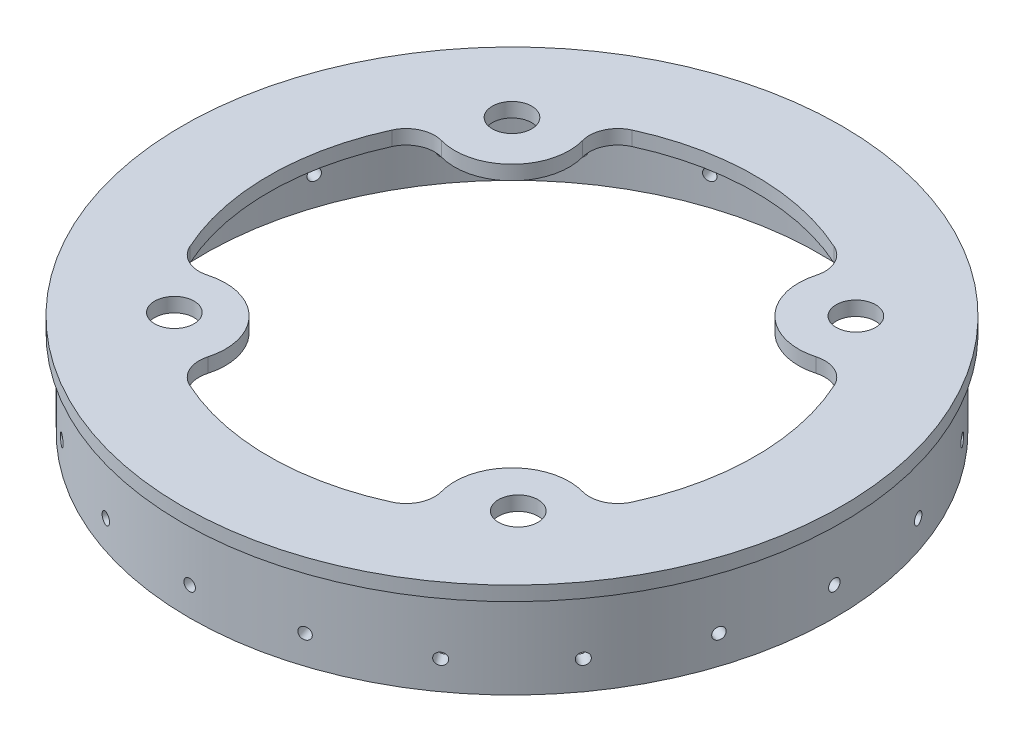
SolidWorks part; units mm, degrees
material "6061-T6 (SS)"
ref_plane "Front Plane" through (0, 0, 0) normal (0, 0, 1) x (1, 0, 0)
ref_plane "Top Plane" through (0, 0, 0) normal (0, 1, 0) x (1, 0, 0)
ref_plane "Right Plane" through (0, 0, 0) normal (1, 0, 0) x (0, 0, -1)
sketch "Sketch1" plane through (0, 0, 0) normal (0, 0, 1) x (1, 0, 0)
  line L0 (149.225, 95.8681) -> (149.225, -49.5637) construction
  line L1 (136.525, 0) -> (142.875, 0)
  line L2 (142.875, 0) -> (142.875, 38.1)
  line L3 (142.875, 38.1) -> (146.05, 38.1)
  line L4 (146.05, 38.1) -> (146.05, 44.45)
  line L5 (146.05, 44.45) -> (136.525, 44.45)
  line L6 (136.525, 44.45) -> (136.525, 0)
  line L7 (0, 75.5952) -> (0, -40.7001) construction
  dimension "D1" = 136.525
  dimension "D2" = 9.525
  dimension "D3" = 6.35
  dimension "D4" = 3.175
  dimension "D5" = 6.35
  dimension "D6" = 44.45
revolve "Revolve1" add sketch "Sketch1" angle 360 about L7
ref_plane "Plane1" through (-142.875, 0, 0) normal (-1, 0, 0) x (0, 0, 1)
sketch "Sketch4" plane through (-142.875, 0, 0) normal (-1, 0, 0) x (0, 0, 1)
  line L0 (-142.875, 38.1) -> (142.875, 38.1) construction
  line L1 (-142.875, 0) -> (142.875, 0) construction
  line L2 (-142.875, 38.1) -> (142.875, 38.1) construction
  line L3 (-142.875, 0) -> (142.875, 0) construction
  line L4 (0, 77.7064) -> (0, -55.6061) construction
hole_wizard "1/4-20 Tapped Hole1" positions "3DSketch1" profile "Sketch5" tap size "1/4-20" standard "ANSI Inch"
sketch3d "3DSketch1"
  line L0 (-142.875, 77.7064, 0) -> (-142.875, -55.6061, 0) construction
  line L1 (-142.875, 0, -142.875) -> (-142.875, 0, 142.875) construction
  point P0 (-142.875, 12.7, 0)
  dimension "D1" = 12.7
sketch "Sketch5" plane through (-142.875, 12.7, 0) normal (0, 1, 0) x (0, 0, 1)
  line L0 (0, 0) -> (0, 314.9078)
  line L1 (0, 314.9078) -> (2.5527, 314.9078)
  line L2 (2.5527, 314.9078) -> (2.5527, 0)
  line L5 (2.5527, 0) -> (0, 0)
  line L11 (0, -6.35) -> (0, 107.95) construction
  dimension "Thread Major Dia." = 5.1054
  dimension "Thru Tap Drill Depth" = 314.9078
pattern_circular "CirPattern2" count 20 over 360 about axis through (0, 75.5952, 0) along (0, 1, 0) of "1/4-20 Tapped Hole1"
sketch "Sketch6" plane through (0, 44.45, 0) normal (0, 1, 0) x (1, 0, 0)
  line L0 (-224.8129, 0) -> (107.7631, 0) construction
  line L1 (0, 113.3938) -> (0, -91.3137) construction
  arc A0 (-91.9187, 56.248) -> (-56.248, 91.9187) centre (-76.2, 76.2) ccw
  arc A1 (56.248, 91.9187) -> (91.9187, 56.248) centre (76.2, 76.2) ccw
  arc A2 (91.9187, -56.248) -> (56.248, -91.9187) centre (76.2, -76.2) ccw
  arc A3 (-56.248, -91.9187) -> (-91.9187, -56.248) centre (-76.2, -76.2) ccw
  arc A4 (-56.248, -91.9187) -> (56.248, -91.9187) centre (0, 0) ccw
  arc A5 (-91.9187, 56.248) -> (-91.9187, -56.248) centre (0, 0) ccw
  arc A6 (56.248, 91.9187) -> (-56.248, 91.9187) centre (0, 0) ccw
  arc A7 (91.9187, -56.248) -> (91.9187, 56.248) centre (0, 0) ccw
  circle A8 centre (0, 0) radius 136.525 construction
  circle A9 centre (0, 0) radius 136.525
  dimension "D5" = 50.8
  dimension "D6" = 215.5261
  dimension "D1" = 152.4
  dimension "D2" = 152.4
  dimension "D3" = 76.2
  dimension "D4" = 76.2
extrude "Boss-Extrude1" add sketch "Sketch6" against normal blind 6.35
fillet "Fillet1" radius 12.7 8 edges at (-91.9187, 41.275, -56.248) (-56.248, 41.275, -91.9187) (56.248, 41.275, -91.9187) (91.9187, 41.275, -56.248) (91.9187, 41.275, 56.248) (56.248, 41.275, 91.9187) (-91.9187, 41.275, 56.248) (-56.248, 41.275, 91.9187)
sketch "Sketch7" plane through (0, 38.1, 0) normal (0, -1, 0) x (1, 0, 0)
  line L0 (-110.9123, 79.6086) -> (-83.0428, 51.7391)
  line L1 (-79.6086, 110.9123) -> (-51.7391, 83.0428)
  line L2 (-132.8233, 132.8233) -> (131.7271, -131.7271) construction
  line L3 (0, 61.9556) -> (0, -61.9427) construction
  circle A0 centre (0, 0) radius 136.525 construction
  circle A2 centre (0, 0) radius 136.525
  circle A3 centre (0, 0) radius 136.525
  dimension "D2" = 45
  dimension "D1" = 0
chamfer "Chamfer1" distance 12.7 angle 45 1 edges at (0, 38.1, 136.525)
sketch "Sketch9" plane through (0, 44.45, 0) normal (0, 1, 0) x (1, 0, 0)
  point P0 (-76.2, 76.2)
  point P1 (76.2, 76.2)
  point P2 (76.2, -73.4305)
  point P3 (-76.2, -73.4305)
  dimension "D1" = 152.4
  dimension "D3" = 76.2
  dimension "D2" = 76.2
hole_wizard "3/4-16 Tapped Hole1" positions "3DSketch3" profile "Sketch10" tap size "3/4-16" standard "ANSI Inch" end condition through all
sketch3d "3DSketch3"
  point P0 (-76.2, 44.45, -76.2)
  point P3 (-76.2, 44.45, 73.4305)
  point P6 (76.2, 44.45, 73.4305)
  point P9 (76.2, 44.45, -76.2)
sketch "Sketch10" plane through (-76.2, 44.45, -76.2) normal (1, 0, 0) x (0, 0, 1)
  line L0 (0, 0) -> (0, 44.45)
  line L1 (0, 44.45) -> (8.7312, 44.45)
  line L2 (8.7312, 44.45) -> (8.7312, 0)
  line L5 (8.7312, 0) -> (0, 0)
  line L11 (0, -6.35) -> (0, 107.95) construction
  dimension "Thru Tap Drill Dia." = 17.4625
  dimension "Thru Tap Drill Depth" = 44.45
cosmetic thread "Hole Thread1" parameters "D2"=19.05
cosmetic thread "Hole Thread2" parameters "D2"=19.05
cosmetic thread "Hole Thread3" parameters "D2"=19.05
cosmetic thread "Hole Thread4" parameters "D2"=19.05
equation "\"D2@Sketch6\"=\"D1@Sketch6\""
equation "\"D3@Sketch6\"=\"D1@Sketch6\"/2"
equation "\"D4@Sketch6\"=\"D3@Sketch6\""
equation "\"D6@Sketch6\"=\"D4@Sketch6\"*sqr( 2)*2"
equation "\"D2@Sketch9\"=\"D1@Sketch9\"/2"
equation "\"D3@Sketch9\"=\"D1@Sketch9\"/2"
